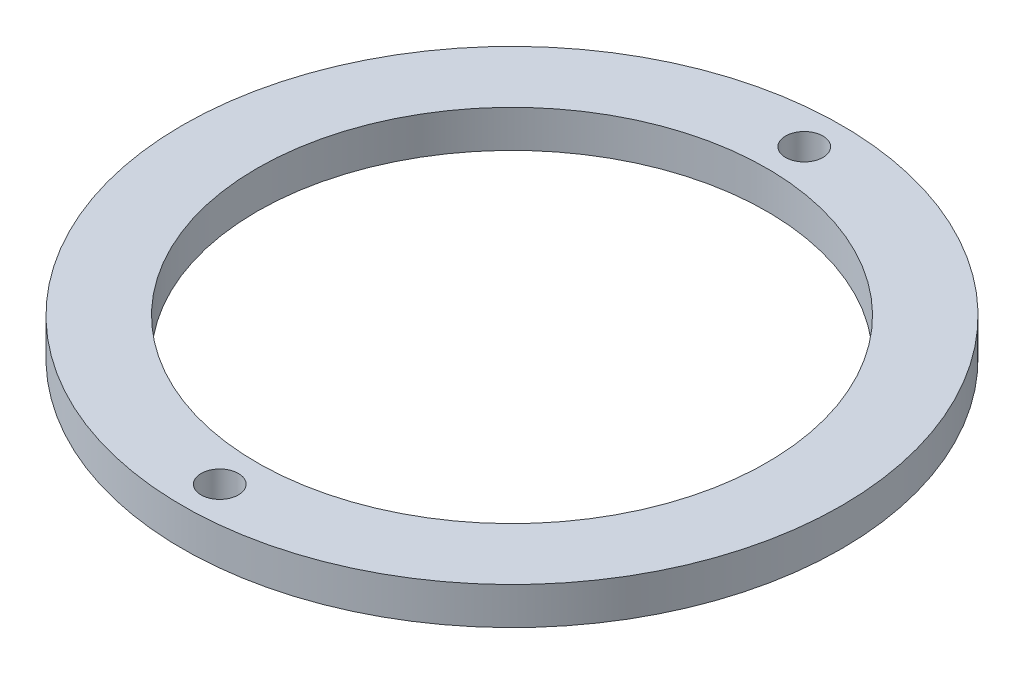
SolidWorks part; units mm, degrees
ref_plane "Спереди" through (0, 0, 0) normal (0, 0, 1) x (1, 0, 0)
ref_plane "Сверху" through (0, 0, 0) normal (0, 1, 0) x (1, 0, 0)
ref_plane "Справа" through (0, 0, 0) normal (1, 0, 0) x (0, 0, -1)
sketch "Эскиз1" plane through (0, 0, 0) normal (0, 0, 1) x (1, 0, 0)
  line L0 (0, 55.8895) -> (0, 15.1289) construction
  line L1 (20.5, 38.6) -> (20.5, 35.6)
  line L2 (20.5, 35.6) -> (26.5, 35.6)
  line L3 (26.5, 35.6) -> (26.5, 38.6)
  line L4 (26.5, 38.6) -> (20.5, 38.6)
revolve "Повернуть1" add sketch "Эскиз1" angle 360 about L0
sketch "Эскиз2" plane through (0, 38.6, 0) normal (0, 1, 0) x (1, 0, 0)
  line L0 (0, 0) -> (0, -29.6343) construction
  line L1 (0, 0) -> (-7.8319, 0) construction
  circle A1 centre (0, -23.5) radius 1.5
  circle A2 centre (0, 0) radius 23.5
  circle A3 centre (0, 0) radius 23.5 construction
  circle A4 centre (0, 23.5) radius 1.5
  dimension "D2" = 3
  dimension "D1" = 3
extrude "Вырез-Вытянуть1" cut sketch "Эскиз2" against normal blind 10
